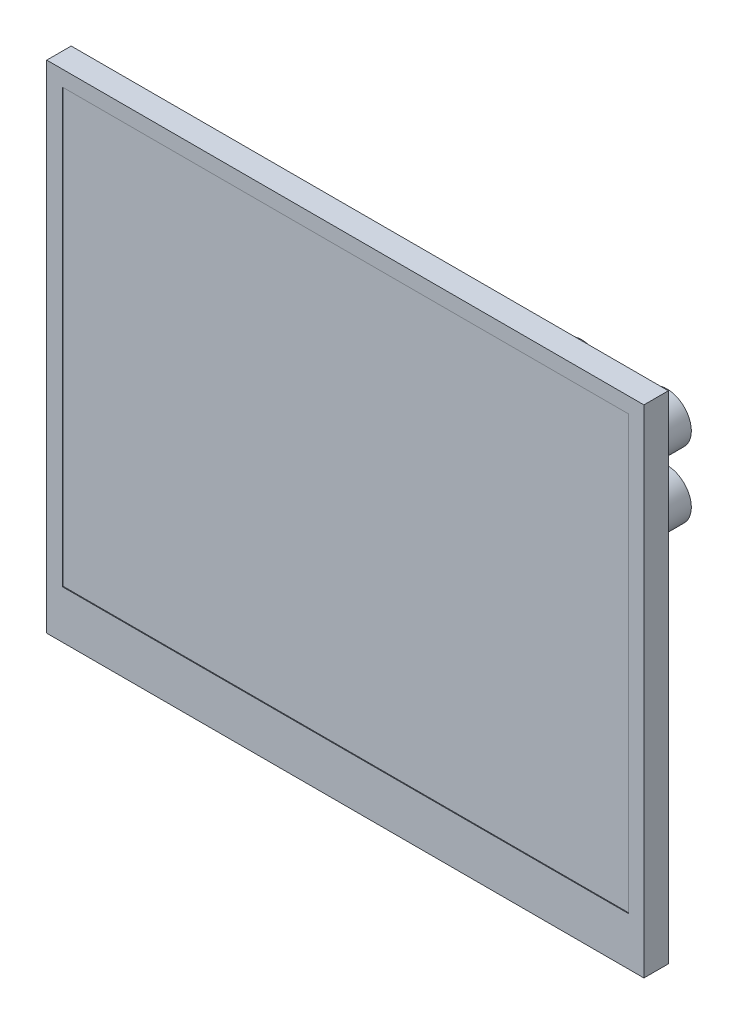
SolidWorks part; units mm, degrees
ref_plane "Front Plane" through (0, 0, 0) normal (0, 0, 1) x (1, 0, 0)
ref_plane "Top Plane" through (0, 0, 0) normal (0, 1, 0) x (1, 0, 0)
ref_plane "Right Plane" through (0, 0, 0) normal (1, 0, 0) x (0, 0, -1)
sketch "Sketch1" plane through (0, 0, 0) normal (0, 0, 1) x (1, 0, 0)
  line L1 (-38.5, -32) -> (38.5, -32)
  line L2 (-38.5, -32) -> (-38.5, 32)
  line L3 (-38.5, 32) -> (38.5, 32)
  line L4 (38.5, -32) -> (38.5, 32)
  line L5 (-38.5, -32) -> (38.5, 32) construction
  line L6 (-38.5, 32) -> (38.5, -32) construction
  point P0 (0, 0)
  dimension "D1" = 64
  dimension "D2" = 77
extrude "Boss-Extrude1" add sketch "Sketch1" along normal mid plane 3.15
sketch "Sketch2" plane through (0, 0, -1.575) normal (0, 0, -1) x (-1, 0, 0)
  line L0 (-38.5, -32) -> (-38.5, 32) construction
  line L1 (-34.5, 23.25) -> (21.5, 23.25)
  line L2 (-34.5, 23.25) -> (-34.5, -6.75)
  line L3 (-34.5, -6.75) -> (21.5, -6.75)
  line L4 (21.5, 23.25) -> (21.5, -6.75)
  line L5 (-38.5, 32) -> (38.5, 32) construction
  dimension "D1" = 30
  dimension "D2" = 56
  dimension "D3" = 4
  dimension "D4" = 8.75
extrude "Boss-Extrude2" add sketch "Sketch2" along normal blind 4
sketch "Sketch3" plane through (0, 0, -5.575) normal (0, 0, -1) x (-1, 0, 0)
  line L0 (-6.1503, 18.9993) -> (0.3497, 18.9993) construction
  line L1 (-6.1503, 20.9993) -> (0.3497, 20.9993)
  line L2 (-6.1503, 16.9993) -> (0.3497, 16.9993)
  circle A0 centre (-28.336, 18.9993) radius 3.125
  circle A1 centre (-17.3559, 18.9993) radius 3.125
  circle A2 centre (-28.336, 10.4705) radius 3.125
  arc A3 (-6.1503, 20.9993) -> (-6.1503, 16.9993) centre (-6.1503, 18.9993) ccw
  arc A4 (0.3497, 16.9993) -> (0.3497, 20.9993) centre (0.3497, 18.9993) ccw
  point P8 (-2.9003, 18.9993)
  point P13 (0, 0)
  point P14 (0, 0)
  dimension "D1" = 6.25
  dimension "D2" = 6.25
  dimension "D3" = 6.25
  dimension "D5" = 2
  dimension "D4" = 6.5
extrude "Boss-Extrude3" add sketch "Sketch3" along normal blind 6
sketch "Sketch4" plane through (0, 0, 1.575) normal (0, 0, 1) x (1, 0, 0)
  line L0 (38.5, 32) -> (-38.5, 32) construction
  line L1 (-36.5, 30) -> (36.5, 30)
  line L2 (-36.5, 30) -> (-36.5, -25.8)
  line L3 (-36.5, -25.8) -> (36.5, -25.8)
  line L4 (36.5, 30) -> (36.5, -25.8)
  line L5 (-38.5, 32) -> (-38.5, -32) construction
  line L6 (38.5, -32) -> (38.5, 32) construction
  line L7 (-38.5, -32) -> (38.5, -32) construction
  dimension "D1" = 2
  dimension "D2" = 2
  dimension "D3" = 2
  dimension "D4" = 6.2
extrude "Cut-Extrude1" cut sketch "Sketch4" against normal blind 0.1
